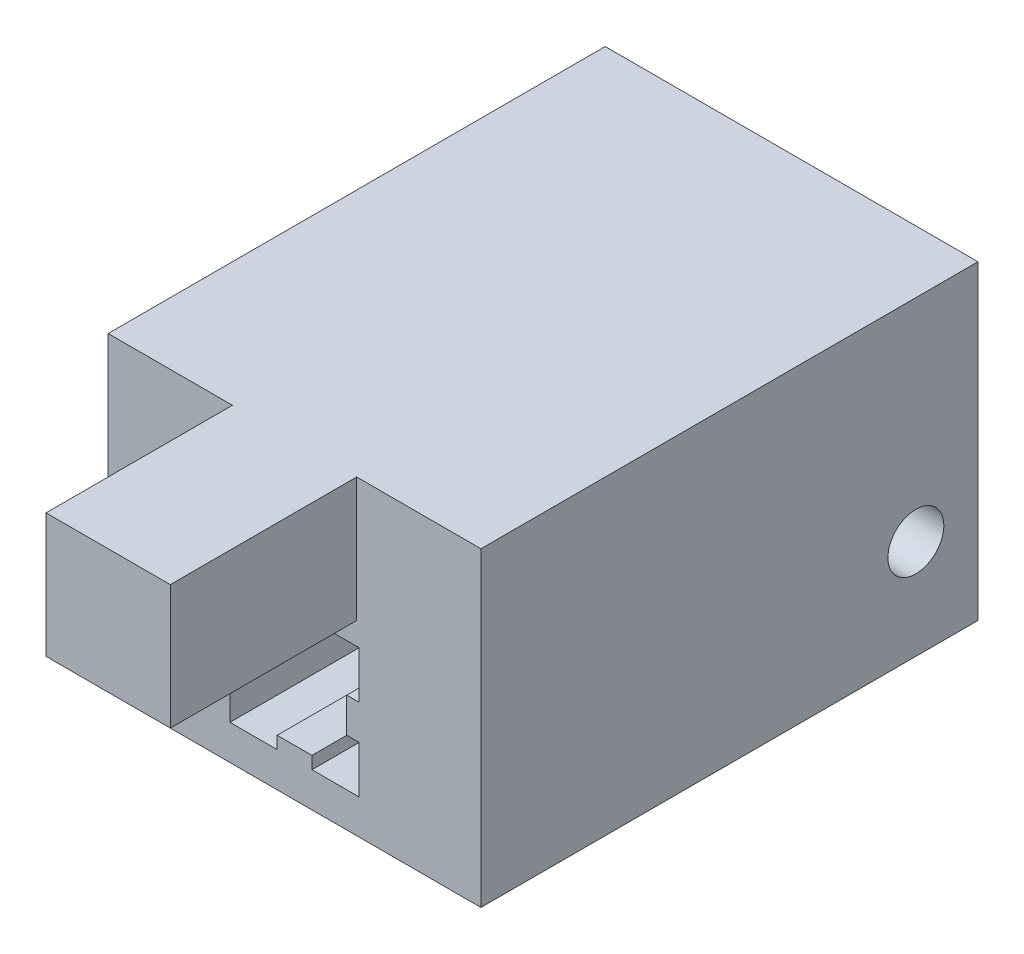
SolidWorks part; units mm, degrees
ref_plane "Front Plane" through (0, 0, 0) normal (0, 0, 1) x (1, 0, 0)
ref_plane "Top Plane" through (0, 0, 0) normal (0, 1, 0) x (1, 0, 0)
ref_plane "Right Plane" through (0, 0, 0) normal (1, 0, 0) x (0, 0, -1)
sketch "Esquisse1" plane through (0, 0, 0) normal (0, 0, 1) x (1, 0, 0)
  line L1 (-15, 12.5) -> (15, 12.5)
  line L2 (-15, 12.5) -> (-15, -12.5)
  line L3 (-15, -12.5) -> (15, -12.5)
  line L4 (15, 12.5) -> (15, -12.5)
  point P4 (0, -12.5)
  point P5 (-15, 0)
  dimension "D1" = 30
  dimension "D2" = 25
extrude "Boss.-Extru.1" add sketch "Esquisse1" along normal blind 40
sketch "Esquisse3" plane through (0, 0, 0) normal (0, 0, -1) x (-1, 0, 0)
  line L0 (-5.2, 0.7) -> (-5.2, -3.1)
  line L1 (-5.2, -3.1) -> (-4.2, -3.1)
  line L2 (-4.2, -3.1) -> (-4.2, -5.9)
  line L3 (-4.2, -5.9) -> (-5.2, -5.9)
  line L4 (-5.2, -5.9) -> (-5.2, -9.7)
  line L5 (-5.2, -9.7) -> (-1.4, -9.7)
  line L6 (-1.4, -9.7) -> (-1.4, -8.7)
  line L7 (-1.4, -8.7) -> (1.4, -8.7)
  line L8 (1.4, -8.7) -> (1.4, -9.7)
  line L9 (1.4, -9.7) -> (5.2, -9.7)
  line L10 (5.2, -9.7) -> (5.2, -5.9)
  line L11 (5.2, -5.9) -> (4.2, -5.9)
  line L12 (4.2, -5.9) -> (4.2, -3.1)
  line L13 (4.2, -3.1) -> (5.2, -3.1)
  line L14 (5.2, -3.1) -> (5.2, 0.7)
  line L15 (5.2, 0.7) -> (1.4, 0.7)
  line L16 (1.4, 0.7) -> (1.4, -0.3)
  line L17 (1.4, -0.3) -> (-1.4, -0.3)
  line L18 (-1.4, -0.3) -> (-1.4, 0.7)
  line L19 (-1.4, 0.7) -> (-5.2, 0.7)
  line L21 (15, -12.5) -> (-15, -12.5) construction
  point P20 (0, -8.7)
  point P21 (1.35, -5.6098)
  point P24 (0, -12.5)
  point P25 (-5.2, 3.5097)
  point P26 (0, 0)
  point P27 (-1.35, -2.2318)
  point P28 (-1.35, -5.8697)
  point P29 (0, 0)
  point P30 (1.35, 1.0698)
  point P31 (3.3288, -0.784)
  point P32 (1.35, -6.6435)
  point P33 (-4.2, -4.5)
  dimension "D1" = 2.8
  dimension "D2" = 10.4
  dimension "D3" = 1
  dimension "D4" = 1
  dimension "D5" = 8
extrude "Enlèv. mat.-Extru.1" cut sketch "Esquisse3" against normal through all
sketch "Esquisse4" plane through (-15, 0, 0) normal (-1, 0, 0) x (0, 0, 1)
  line L1 (0, -5.9) -> (0, -3.1) construction
  line L2 (0, 12.5) -> (0, -12.5) construction
  circle A0 centre (5, -4.5) radius 2.25
  point P2 (5.9282, 0)
  point P5 (0, -4.5)
  dimension "D1" = 4.5
  dimension "D2" = 5
extrude "Enlèv. mat.-Extru.2" cut sketch "Esquisse4" against normal blind 8
sketch "Esquisse5" plane through (15, 0, 0) normal (1, 0, 0) x (0, 0, -1)
  line L0 (0, -3.1) -> (0, -5.9) construction
  line L1 (0, -12.5) -> (0, 12.5) construction
  circle A0 centre (-5, -4.5) radius 2.25
  point P4 (0, -4.5)
  dimension "D2" = 4.5
  dimension "D1" = 5
extrude "Enlèv. mat.-Extru.3" cut sketch "Esquisse5" against normal blind 8
sketch "Esquisse6" plane through (0, 0, 40) normal (0, 0, 1) x (1, 0, 0)
  line L0 (15, 12.5) -> (-15, 12.5) construction
  line L1 (-5, 12.5) -> (5, 12.5)
  line L2 (-5, 12.5) -> (-5, 2.5)
  line L3 (-5, 2.5) -> (5, 2.5)
  line L4 (5, 12.5) -> (5, 2.5)
  point P7 (-5.2, 3.2)
  point P9 (4.9816, 5.0162)
  point P10 (-2.7897, 12.5)
  point P11 (0, 12.5)
  point P12 (0, 12.5)
  dimension "D1" = 10
  dimension "D2" = 10
extrude "Boss.-Extru.2" add sketch "Esquisse6" along normal blind 15
